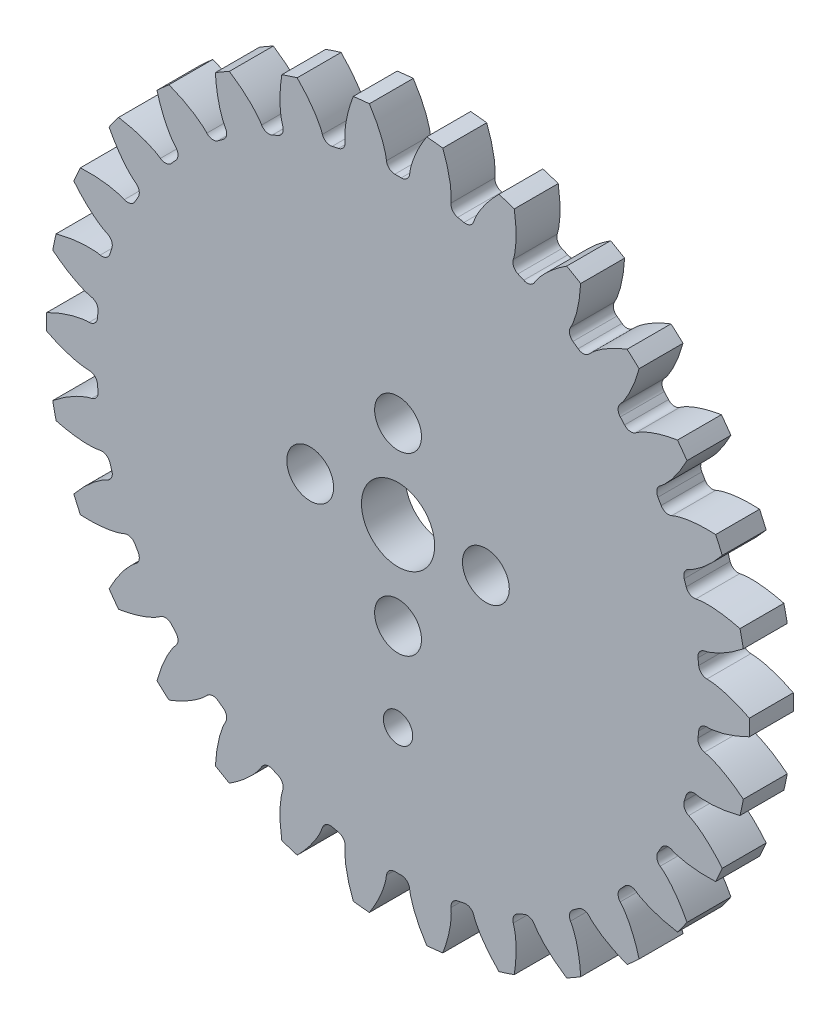
SolidWorks part; units mm, degrees
material "Hexcel AS4C (3000 丝)"
ref_plane "前视基准面" through (0, 0, 0) normal (0, 0, 1) x (1, 0, 0)
ref_plane "上视基准面" through (0, 0, 0) normal (0, 1, 0) x (1, 0, 0)
ref_plane "右视基准面" through (0, 0, 0) normal (1, 0, 0) x (0, 0, -1)
ref_axis "Axis1" through (0, 0, -88.99) along (0, 0, 1)
sketch "草图1" plane through (0, 0, 0) normal (0, 0, 1) x (1, 0, 0)
  circle A0 centre (0, 0) radius 24
extrude "LaShenA" add sketch "草图1" along normal blind 3
sketch "SketchA" plane through (0, 0, 3) normal (0, 0, 1) x (1, 0, 0)
  line L0 (0, 0) -> (0, 24) construction
  arc A0 (0.2184, 20.6238) -> (-0.2184, 20.6238) centre (0, 0) ccw
  arc A1 (2.5339, 24.7321) -> (-2.5339, 24.7321) centre (0, 0) ccw
  arc A2 (-0.2184, 20.6238) -> (-0.7909, 21.1307) centre (-0.2244, 21.1938) cw
  arc A3 (0.7909, 21.1307) -> (0.2184, 20.6238) centre (0.2244, 21.1938) cw
  circle A4 centre (0, 0) radius 21.1431 construction
  circle A5 centre (0, 0) radius 24 construction
  circle A6 centre (0, 0) radius 20.625 construction
  circle A7 centre (0, 0) radius 22.5 construction
  spline S0 degree 3 poles (0.7909, 21.1307) (0.7927, 21.1471) (0.7998, 21.2085) (0.8112, 21.291) (0.8279, 21.3808) (0.8427, 21.4528) (0.8612, 21.5338) (0.8836, 21.6234) (0.9104, 21.7217) (0.9419, 21.8284) (0.9785, 21.9433) (1.0206, 22.0664) (1.0685, 22.1974) (1.1226, 22.3362) (1.1831, 22.4824) (1.2506, 22.636) (1.3252, 22.7967) (1.4073, 22.9642) (1.4973, 23.1383) (1.5954, 23.3187) (1.702, 23.5052) (1.8173, 23.6975) (1.9417, 23.8953) (2.0754, 24.0982) (2.27, 24.3805) (2.4255, 24.5913) (2.5339, 24.7321) knots 0.114617 0.114617 0.114617 0.114617 0.125462 0.155251 0.169305 0.18542 0.203596 0.223834 0.246133 0.270493 0.296915 0.325398 0.355942 0.388548 0.423215 0.459943 0.498732 0.539583 0.582495 0.627469 0.674504 0.7236 0.774757 0.827976 0.883256 1 1 1 1
  spline S1 degree 3 poles (-0.7909, 21.1307) (-0.7927, 21.1471) (-0.7998, 21.2085) (-0.8112, 21.291) (-0.8279, 21.3808) (-0.8427, 21.4528) (-0.8612, 21.5338) (-0.8836, 21.6234) (-0.9104, 21.7217) (-0.9419, 21.8284) (-0.9785, 21.9433) (-1.0206, 22.0664) (-1.0685, 22.1974) (-1.1226, 22.3362) (-1.1831, 22.4824) (-1.2506, 22.636) (-1.3252, 22.7967) (-1.4073, 22.9642) (-1.4973, 23.1383) (-1.5954, 23.3187) (-1.702, 23.5052) (-1.8173, 23.6975) (-1.9417, 23.8953) (-2.0754, 24.0982) (-2.27, 24.3805) (-2.4255, 24.5913) (-2.5339, 24.7321) knots 0.114617 0.114617 0.114617 0.114617 0.125462 0.155251 0.169305 0.18542 0.203596 0.223834 0.246133 0.270493 0.296915 0.325398 0.355942 0.388548 0.423215 0.459943 0.498732 0.539583 0.582495 0.627469 0.674504 0.7236 0.774757 0.827976 0.883256 1 1 1 1
  dimension "D1" = 0.57
  dimension "Db" = 42.2862
  dimension "Da" = 48
  dimension "Df" = 41.25
  dimension "Dn" = 45
extrude "Cut-ExtrudeA" cut sketch "SketchA" against normal blind 3
pattern_circular "www.KYTool.cn" count 30 over 360 about axis through (0, 0, -88.99) along (0, 0, 1) of "Cut-ExtrudeA"
sketch "草图3" plane through (0, 0, 3) normal (0, 0, 1) x (1, 0, 0)
  line L0 (-1000, 0) -> (49000, 0) construction
  circle A0 centre (6, 0) radius 1.6
  circle A1 centre (0, -6) radius 1.6
  circle A2 centre (-6, 0) radius 1.6
  circle A3 centre (0, 6) radius 1.6
  circle A4 centre (0, 0) radius 2.5
  point P14 (0, 0)
  dimension "D1" = 3.2
  dimension "D2" = 6
  dimension "D4" = 5
  dimension "D3" = 4
extrude "切除-拉伸2" cut sketch "草图3" against normal through all
sketch "草图4" plane through (0, 0, 3) normal (0, 0, 1) x (1, 0, 0)
  circle A0 centre (0, -12) radius 1
  dimension "D1" = 2
  dimension "D2" = 12
extrude "切除-拉伸3" cut sketch "草图4" against normal through all
